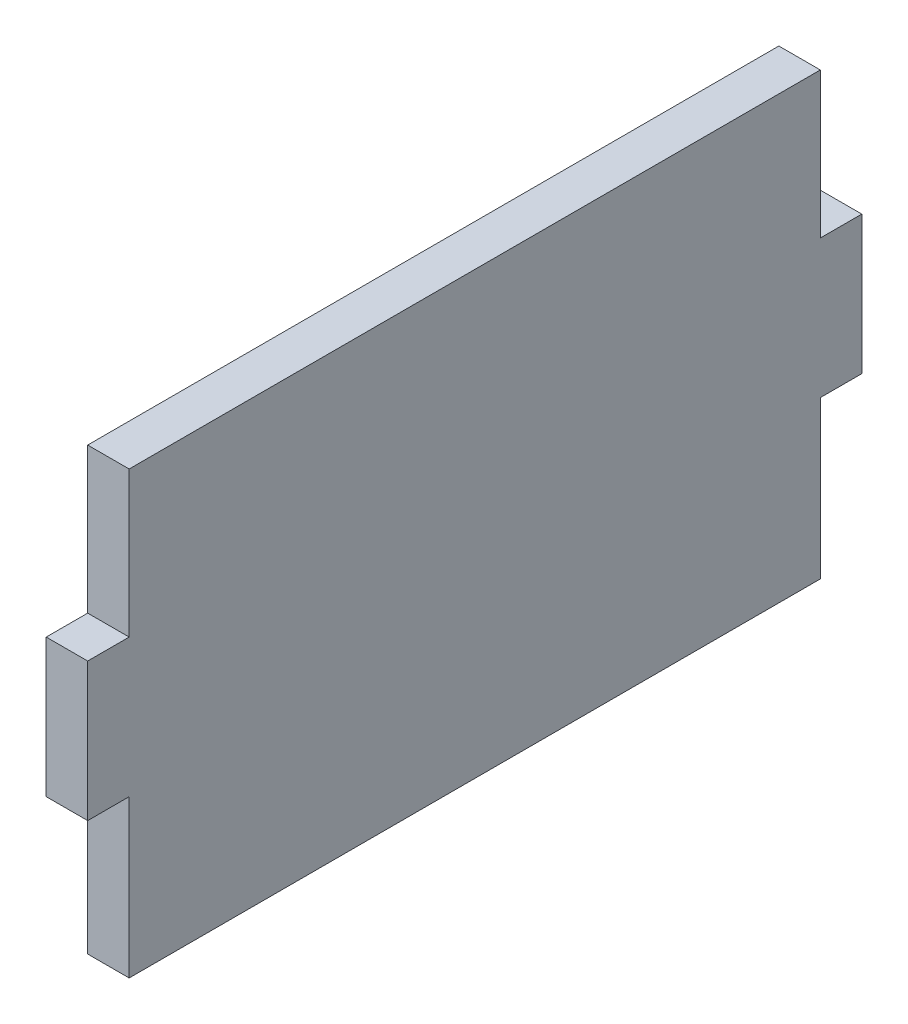
SolidWorks part; units mm, degrees
ref_plane "Front Plane" through (0, 0, 0) normal (0, 0, 1) x (1, 0, 0)
ref_plane "Top Plane" through (0, 0, 0) normal (0, 1, 0) x (1, 0, 0)
ref_plane "Right Plane" through (0, 0, 0) normal (1, 0, 0) x (0, 0, -1)
sketch "Sketch2" plane through (0, 0, 0) normal (1, 0, 0) x (0, 0, -1)
  line L0 (0, 31.89) -> (0, 21.36) construction
  line L1 (0, 0) -> (50, 0)
  line L2 (0, 0) -> (0, 11.36)
  line L3 (0, 31.89) -> (50, 31.89)
  line L4 (50, 0) -> (50, 11.36)
  line L5 (0, 21.36) -> (0, 31.89)
  line L6 (0, 21.36) -> (-3, 21.36)
  line L8 (0, 11.36) -> (-3, 11.36)
  line L9 (-3, 21.36) -> (-3, 11.36)
  line L10 (25, 31.89) -> (25, 0) construction
  line L11 (50, 11.36) -> (53, 11.36)
  line L12 (53, 21.36) -> (53, 11.36)
  line L13 (50, 21.36) -> (53, 21.36)
  line L14 (50, 21.36) -> (50, 31.89)
  dimension "D1" = 50
  dimension "D2" = 31.89
  dimension "D3" = 10.53
  dimension "D4" = 10
  dimension "D5" = 3
extrude "Boss-Extrude1" add sketch "Sketch2" along normal blind 3
